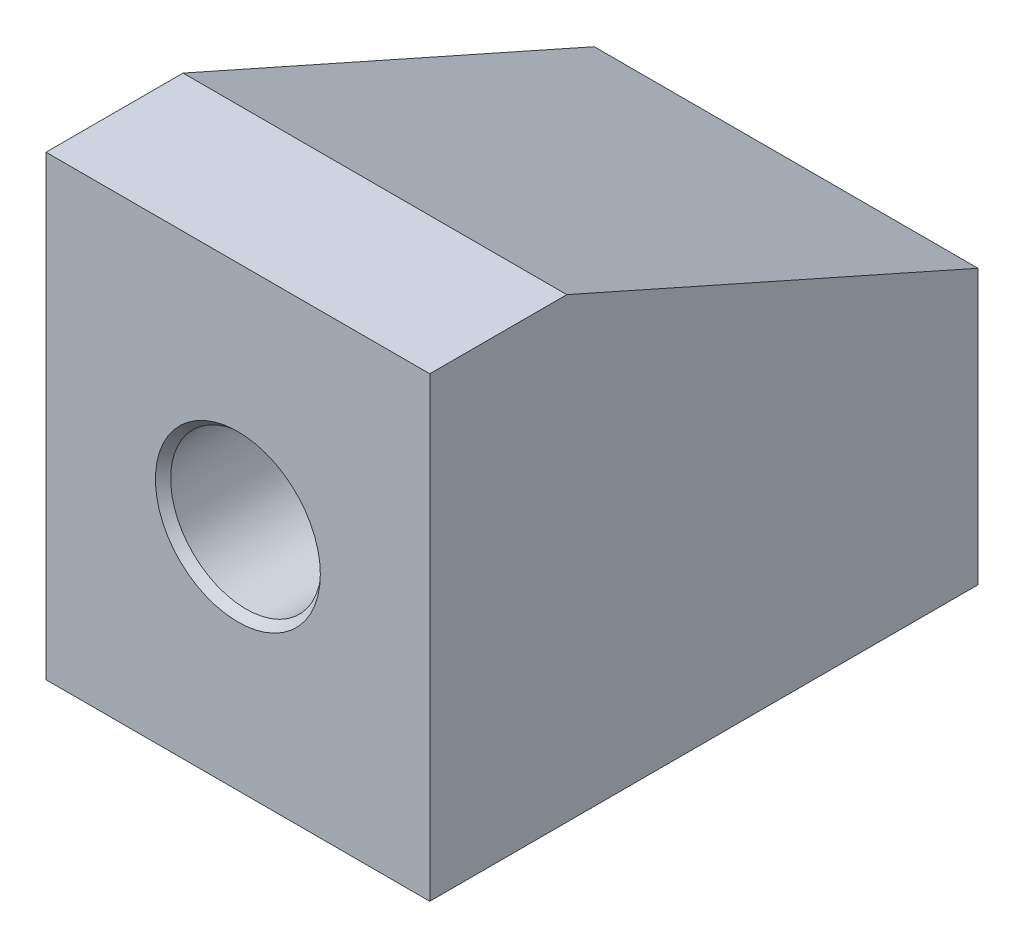
SolidWorks part; units mm, degrees
ref_plane "Piano frontale" through (0, 0, 0) normal (0, 0, 1) x (1, 0, 0)
ref_plane "Piano superiore" through (0, 0, 0) normal (0, 1, 0) x (1, 0, 0)
ref_plane "Piano destro" through (0, 0, 0) normal (1, 0, 0) x (0, 0, -1)
sketch "Schizzo1" plane through (0, 0, 0) normal (1, 0, 0) x (0, 0, -1)
  line L0 (-30, 50) -> (-30, 0)
  line L1 (-30, 0) -> (30, 0)
  line L2 (30, 0) -> (30, 30)
  line L3 (30, 30) -> (-15, 50)
  line L4 (-15, 50) -> (-30, 50)
  dimension "D1" = 60
  dimension "D2" = 30
  dimension "D3" = 15
  dimension "D4" = 50
extrude "Estrusione-Estrusione1" add sketch "Schizzo1" along normal blind 42
sketch "Schizzo2" plane through (0, 0, 30) normal (0, 0, 1) x (1, 0, 0)
  line L0 (42, 50) -> (42, 0) construction
  line L1 (42, 0) -> (0, 0) construction
  point P0 (21, 25)
  dimension "D1" = 21
  dimension "D2" = 25
hole_wizard "Foro filettato M18x1.5-1" positions "Schizzo3" profile "Schizzo4" tap size "M18x1.5" standard "Ansi Metric"
sketch "Schizzo3" plane through (0, 0, 30) normal (0, 0, 1) x (1, 0, 0)
  point P0 (21, 25)
sketch "Schizzo4" plane through (21, 25, 30) normal (1, 0, 0) x (0, -1, 0)
  line L0 (0, 0) -> (0, 43.5)
  line L1 (0, 43.5) -> (8.25, 38.5429)
  line L2 (8.25, 38.5429) -> (8.25, 0.8915)
  line L3 (8.25, 0.8915) -> (9.025, 0)
  line L5 (9.025, 0) -> (0, 0)
  line L6 (-8.25, 0.8915) -> (-9.025, 0) construction
  line L10 (0, 43.5) -> (-8.25, 38.5429) construction
  line L11 (0, -6.35) -> (0, 107.95) construction
  dimension "Tap Drill Dia." = 16.5
  dimension "Tap Drill Depth" = 43.5
  dimension "Near C'Sink Dia." = 18.05
  dimension "Near C'Sink Angle" = 82
  dimension "Drill Angle" = 118
cosmetic thread "Filettatura del foro1" parameters "D1"=36, "D2"=18
